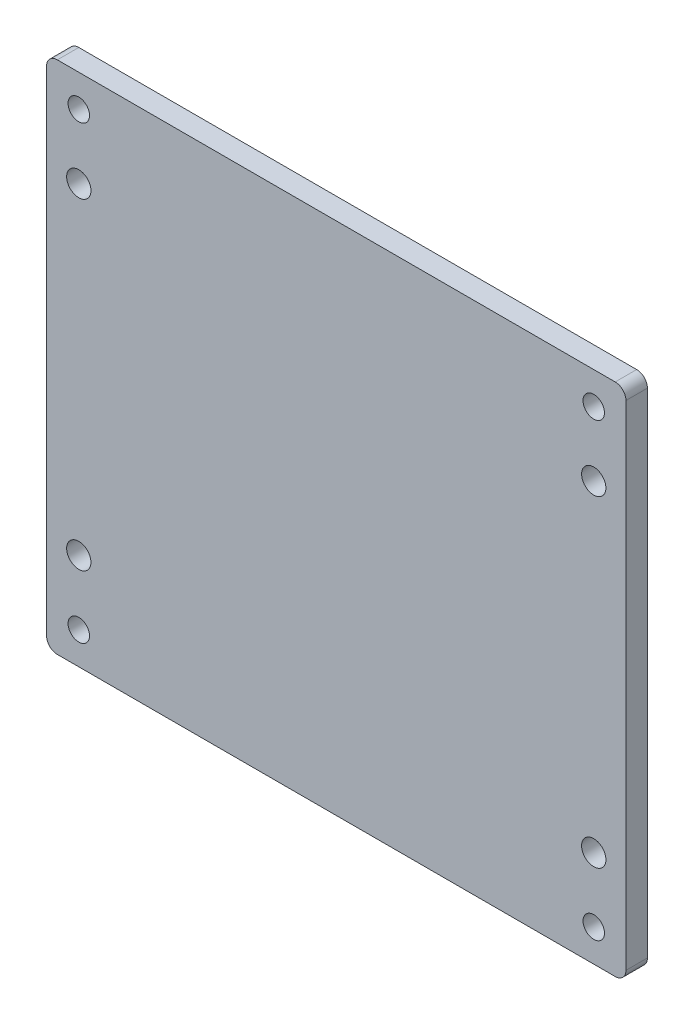
SolidWorks part; units mm, degrees
ref_plane "Alzado" through (0, 0, 0) normal (0, 0, 1) x (1, 0, 0)
ref_plane "Planta" through (0, 0, 0) normal (0, 1, 0) x (1, 0, 0)
ref_plane "Vista lateral" through (0, 0, 0) normal (1, 0, 0) x (0, 0, -1)
sketch "Model" plane through (0, 0, 0) normal (0, 0, 1) x (1, 0, 0)
  line L0 (85.4827, 227.2463) -> (7.4781, 227.2463)
  line L1 (5.9781, 228.7463) -> (5.9781, 297.7487)
  line L2 (7.4781, 299.2487) -> (85.4827, 299.2487)
  line L3 (86.9827, 297.7487) -> (86.9827, 228.7463)
  circle A0 centre (82.483, 294.7487) radius 1.5
  circle A1 centre (10.4781, 231.7459) radius 1.5
  circle A2 centre (82.483, 231.7459) radius 1.5
  circle A3 centre (10.4781, 294.7487) radius 1.5
  circle A4 centre (10.4781, 240.7456) radius 1.7
  circle A5 centre (10.4781, 285.749) radius 1.7
  circle A6 centre (82.483, 240.7456) radius 1.7
  circle A7 centre (82.483, 285.749) radius 1.7
  arc A8 (7.4781, 299.2487) -> (5.9781, 297.7487) centre (7.4781, 297.7487) ccw
  arc A9 (86.9827, 297.7487) -> (85.4827, 299.2487) centre (85.4827, 297.7487) ccw
  arc A10 (85.4827, 227.2463) -> (86.9827, 228.7463) centre (85.4827, 228.7463) ccw
  arc A11 (5.9781, 228.7463) -> (7.4781, 227.2463) centre (7.4781, 228.7463) ccw
extrude "Saliente-Extruir1" add sketch "Model" along normal blind 3
